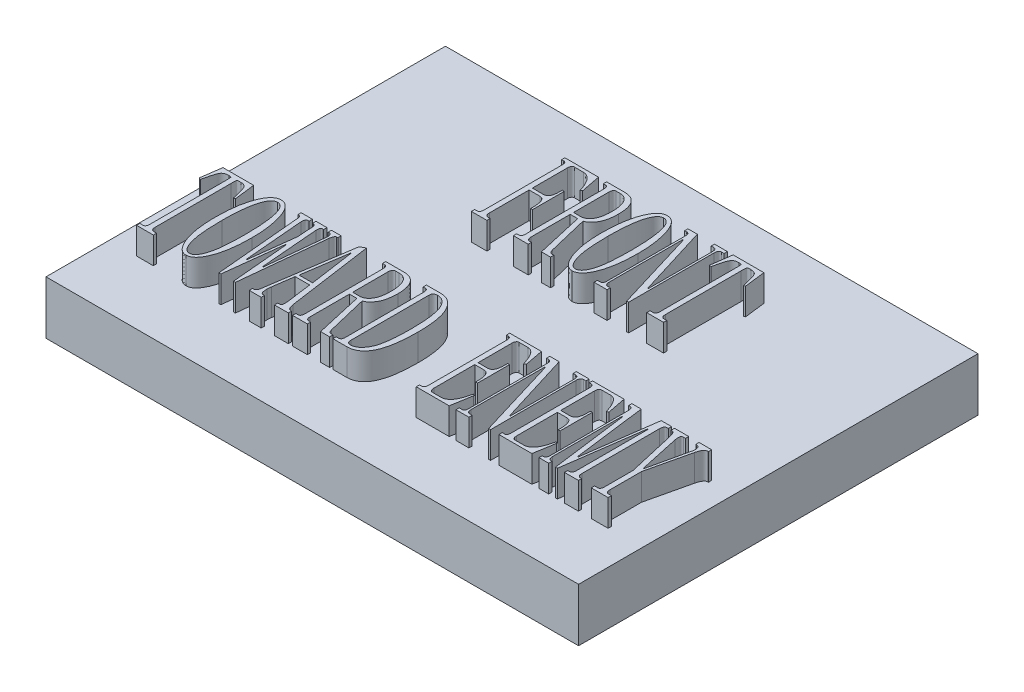
SolidWorks part; units mm, degrees
ref_plane "前视基准面" through (0, 0, 0) normal (0, 0, 1) x (1, 0, 0)
ref_plane "上视基准面" through (0, 0, 0) normal (0, 1, 0) x (1, 0, 0)
ref_plane "右视基准面" through (0, 0, 0) normal (1, 0, 0) x (0, 0, -1)
other "Configuration Table"
sketch "草图1" plane through (0, 0, 0) normal (0, 1, 0) x (1, 0, 0)
  line L1 (-10, -7.5) -> (10, -7.5)
  line L2 (-10, -7.5) -> (-10, 7.5)
  line L3 (-10, 7.5) -> (10, 7.5)
  line L4 (10, -7.5) -> (10, 7.5)
  line L5 (-10, -7.5) -> (10, 7.5) construction
  line L6 (-10, 7.5) -> (10, -7.5) construction
  point P0 (0, 0)
  dimension "D1" = 15
  dimension "D2" = 20
extrude "凸台-拉伸1" add sketch "草图1" along normal blind 2
sketch "草图4" plane through (0, 2, 0) normal (0, 1, 0) x (1, 0, 0)
  text T0 "     FRONT\r\n TOWARD ENEMY" font "宋体" height 3.5
extrude "凸台-拉伸2" add sketch "草图4" along normal blind 1
